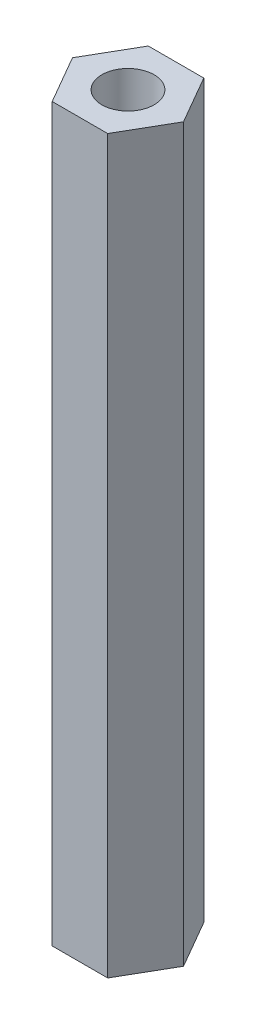
SolidWorks part; units mm, degrees
ref_plane "前视基准面" through (0, 0, 0) normal (0, 0, 1) x (1, 0, 0)
ref_plane "上视基准面" through (0, 0, 0) normal (0, 1, 0) x (1, 0, 0)
ref_plane "右视基准面" through (0, 0, 0) normal (1, 0, 0) x (0, 0, -1)
sketch "草图1" plane through (0, 0, 0) normal (0, 1, 0) x (1, 0, 0)
  line L1 (1.3279, -2.3) -> (2.6558, 0)
  line L2 (2.6558, 0) -> (1.3279, 2.3)
  line L3 (1.3279, 2.3) -> (-1.3279, 2.3)
  line L4 (-1.3279, 2.3) -> (-2.6558, 0)
  line L5 (-2.6558, 0) -> (-1.3279, -2.3)
  line L6 (-1.3279, -2.3) -> (1.3279, -2.3)
  circle A0 centre (0, 0) radius 2.3 construction
  dimension "D1" = 4.6
extrude "凸台-拉伸1" add sketch "草图1" along normal mid plane 35
hole_wizard "M3 螺纹孔1" positions "3D草图2" profile "草图3" tap size "M3" standard "GB" end condition up to next
sketch3d "3D草图2"
  point P0 (0, 0, 0)
  point P3 (0, 0, 0)
  point P5 (0, 17.5, 0)
sketch "草图3" plane through (0, 17.5, 0) normal (1, 0, 0) x (0, 0, 1)
  line L0 (0, 0) -> (0, 35.001)
  line L1 (0, 35.001) -> (1.25, 35.001)
  line L2 (1.25, 35.001) -> (1.25, 0)
  line L5 (1.25, 0) -> (0, 0)
  line L11 (0, -6.35) -> (0, 107.95) construction
  dimension "通孔螺纹孔钻头直径" = 2.5
  dimension "通孔螺纹孔钻头深度" = 35.001
cosmetic thread "孔螺蚊线1" parameters "D2"=3
cosmetic thread "孔螺蚊线2" parameters "D2"=3
cosmetic thread "孔螺蚊线3" parameters "D2"=3
